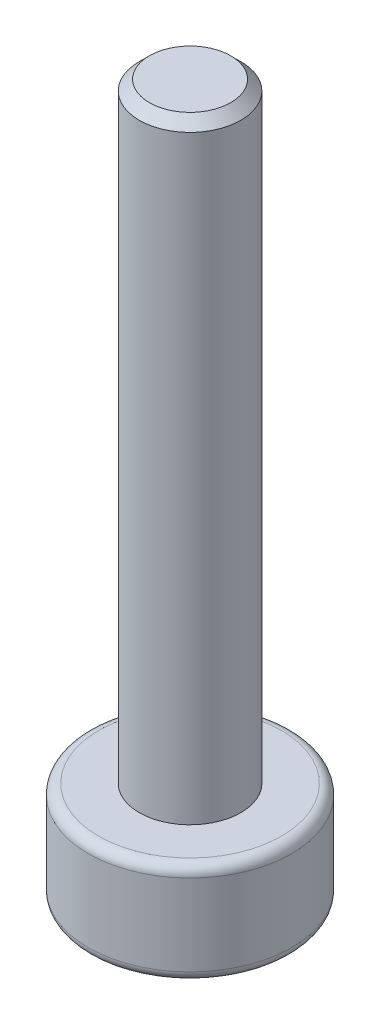
SolidWorks part; units mm, degrees
material "AISI 304"
ref_plane "前视基准面" through (0, 0, 0) normal (0, 0, 1) x (1, 0, 0)
ref_plane "上视基准面" through (0, 0, 0) normal (0, 1, 0) x (1, 0, 0)
ref_plane "右视基准面" through (0, 0, 0) normal (1, 0, 0) x (0, 0, -1)
sketch "草图2" plane through (0, 0, 0) normal (0, 1, 0) x (1, 0, 0)
  circle A0 centre (0, 0) radius 2
  dimension "D1" = 4
extrude "凸台-拉伸1" add sketch "草图2" along normal blind 2
sketch "草图3" plane through (0, 2, 0) normal (0, 1, 0) x (1, 0, 0)
  circle A0 centre (0, 0) radius 1
  dimension "D1" = 2
extrude "凸台-拉伸2" add sketch "草图3" along normal blind 12
fillet "圆角1" radius 0.2 2 edges at (0, 2, 2) (0, 0, 2)
sketch "草图4" plane through (0, 0, 0) normal (0, -1, 0) x (1, 0, 0)
  circle A0 centre (0, 0) radius 0.765
  dimension "D1" = 1.53
extrude "切除-拉伸1" cut sketch "草图4" against normal blind 1.52
chamfer "倒角1" distance 0.1 angle 45 1 edges at (0, 0, -0.765)
chamfer "倒角2" distance 0.2 angle 45 1 edges at (0, 14, 1)
